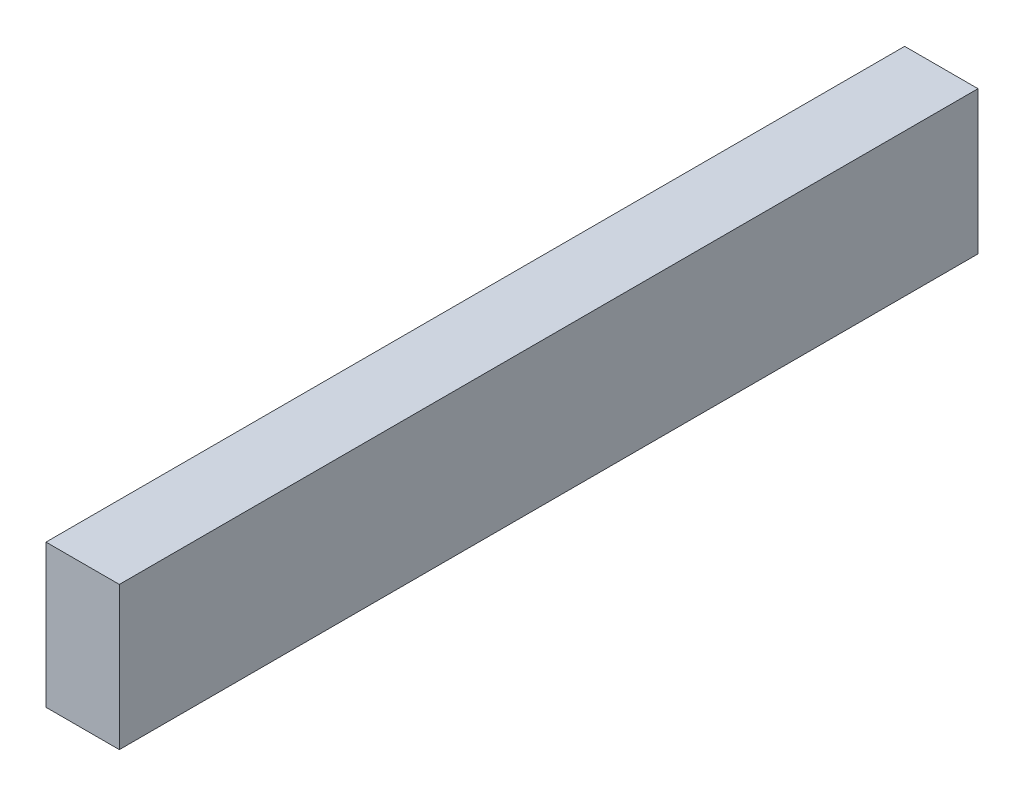
SolidWorks part; units mm, degrees
ref_plane "正面" through (0, 0, 0) normal (0, 0, 1) x (1, 0, 0)
ref_plane "平面" through (0, 0, 0) normal (0, 1, 0) x (1, 0, 0)
ref_plane "右側面" through (0, 0, 0) normal (1, 0, 0) x (0, 0, -1)
sketch "ｽｹｯﾁ1" plane through (0, 0, 0) normal (0, 1, 0) x (1, 0, 0)
  line L1 (0, 0) -> (2.05, 0)
  line L2 (0, 0) -> (0, 24)
  line L3 (0, 24) -> (2.05, 24)
  line L4 (2.05, 0) -> (2.05, 24)
  dimension "D1" = 2.05
  dimension "D2" = 24
extrude "ﾎﾞｽ - 押し出し2" add sketch "ｽｹｯﾁ1" along normal blind 4
